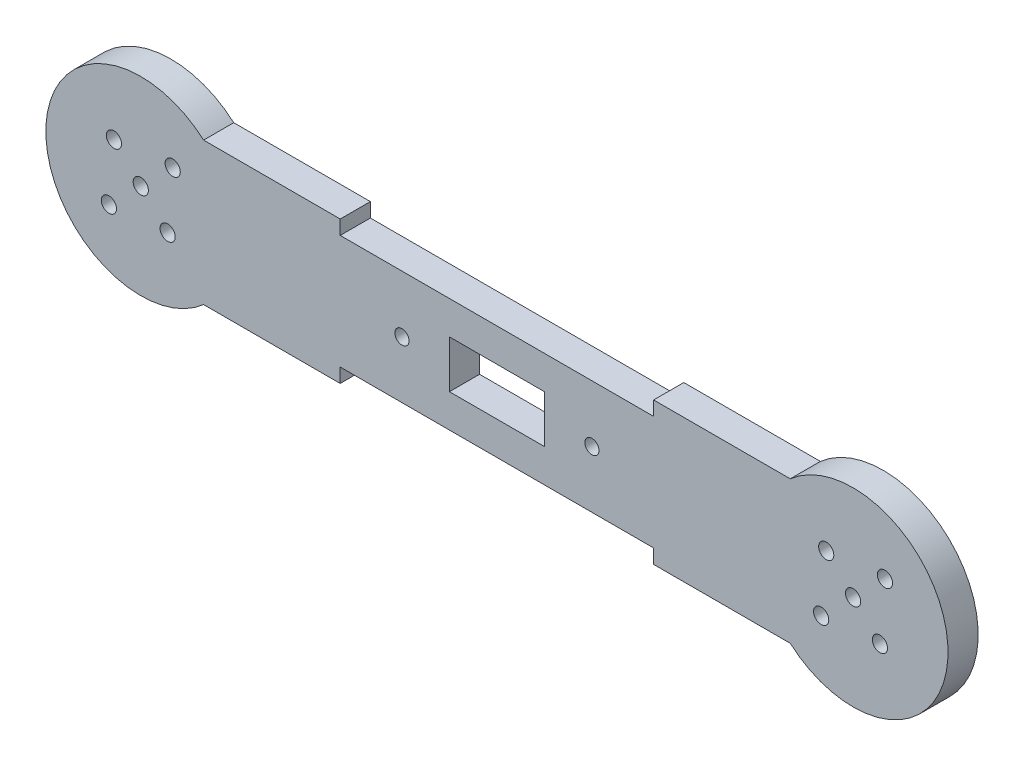
SolidWorks part; units mm, degrees
ref_plane "Front Plane" through (0, 0, 0) normal (0, 0, 1) x (1, 0, 0)
ref_plane "Top Plane" through (0, 0, 0) normal (0, 1, 0) x (1, 0, 0)
ref_plane "Right Plane" through (0, 0, 0) normal (1, 0, 0) x (0, 0, -1)
sketch "Sketch3" plane through (0, 0, 0) normal (0, 0, 1) x (1, 0, 0)
  line L0 (104.5, 0) -> (-104.5, 0) construction
  line L2 (61.7712, -15) -> (-61.7712, -15)
  line L4 (61.7712, 15) -> (-61.7712, 15)
  line L5 (-10, 5) -> (10, 5)
  line L6 (-10, 5) -> (-10, -5)
  line L7 (-10, -5) -> (10, -5)
  line L8 (10, 5) -> (10, -5)
  line L9 (-10, 5) -> (10, -5) construction
  line L10 (-10, -5) -> (10, 5) construction
  arc A0 (-61.7712, 15) -> (-61.7712, -15) centre (-75, 0) ccw
  arc A1 (61.7712, -15) -> (61.7712, 15) centre (75, 0) ccw
  circle A14 centre (-20, 0) radius 1.5
  circle A15 centre (20, 0) radius 1.5
  point P6 (0, 0)
  point P30 (0, 0)
  dimension "D1" = 40
  dimension "D2" = 40
  dimension "D22" = 3
  dimension "D23" = 3
  dimension "D3" = 150
  dimension "D4" = 75
  dimension "D5" = 30
  dimension "D24" = 20
  dimension "D25" = 20
  dimension "D26" = 20
  dimension "D27" = 10
  dimension "D28" = 15
extrude "Boss-Extrude1" add sketch "Sketch3" along normal blind 6.35
hole_wizard "M3 Clearance Hole1" positions "Sketch5" profile "Sketch6" hole size "M3" standard "ANSI Metric"
sketch "Sketch5" plane through (0, 0, 0) normal (0, 0, -1) x (-1, 0, 0)
  line L0 (82.6791, -7.6791) -> (67.3209, 7.6791) construction
  line L2 (3.4925, 0) -> (-3.4925, 0) construction
  line L3 (67.3209, -7.6791) -> (82.6791, 7.6791) construction
  line L4 (0, 32.8384) -> (0, -32.8384) construction
  line L6 (-67.3209, -7.6791) -> (-82.6791, 7.6791) construction
  line L7 (-82.6791, -7.6791) -> (-67.3209, 7.6791) construction
  circle A0 centre (75, 0) radius 8 construction
  circle A1 centre (75, 0) radius 9.5 construction
  circle A2 centre (-75, 0) radius 9.5 construction
  circle A3 centre (-75, 0) radius 8 construction
  point P13 (75, 0)
  point P54 (0, 0)
  point P69 (-75, 0)
  point P74 (-69.3431, 5.6569)
  point P76 (-80.6569, -5.6569)
  point P78 (-81.7175, 6.7175)
  point P80 (-68.2825, -6.7175)
  point P85 (68.2825, 6.7175)
  point P92 (80.6569, 5.6569)
  point P94 (69.3431, -5.6569)
  point P99 (81.7175, -6.7175)
  dimension "D1" = 19
  dimension "D2" = 16
  dimension "D3" = 45
  dimension "D4" = 2
sketch "Sketch6" plane through (-81.7175, -6.7175, 0) normal (1, 0, 0) x (0, 1, 0)
  line L0 (0, 0) -> (0, 8.4614)
  line L1 (0, 8.4614) -> (1.6, 7.5)
  line L2 (1.6, 7.5) -> (1.6, 0)
  line L5 (1.6, 0) -> (0, 0)
  line L10 (0, 8.4614) -> (-1.6, 7.5) construction
  line L11 (0, -6.35) -> (0, 107.95) construction
  dimension "Hole Dia." = 3.2
  dimension "Hole Depth" = 7.5
  dimension "Drill Angle" = 118
sketch "Sketch4" plane through (0, 0, 0) normal (0, 0, -1) x (-1, 0, 0)
  line L1 (33, 15) -> (-33, 15)
  line L2 (33, 15) -> (33, 12)
  line L3 (33, 12) -> (-33, 12)
  line L4 (-33, 15) -> (-33, 12)
  line L5 (33, 15) -> (-33, 12) construction
  line L6 (33, 12) -> (-33, 15) construction
  line L7 (0, 0) -> (0, -22.8749) construction
  line L8 (0, 3.4925) -> (0, -3.4925) construction
  line L9 (-61.7712, 15) -> (61.7712, 15) construction
  point P0 (0, 13.5)
  dimension "D1" = 3
  dimension "D2" = 66
extrude "Cut-Extrude1" cut sketch "Sketch4" against normal blind 10
mirror "Mirror1" about plane through (0, 0, 0) normal (0, 1, 0) of "Cut-Extrude1"
